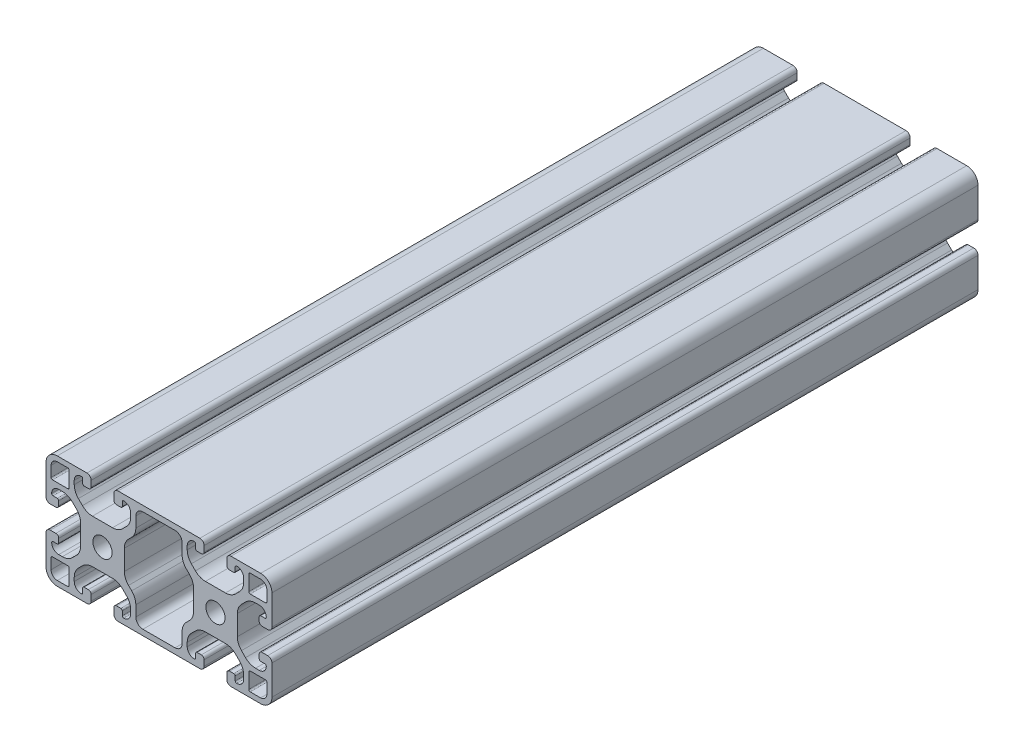
SolidWorks part; units mm, degrees
ref_plane "Plan de face" through (0, 0, 0) normal (0, 0, 1) x (1, 0, 0)
ref_plane "Plan de dessus" through (0, 0, 0) normal (0, 1, 0) x (1, 0, 0)
ref_plane "Plan de droite" through (0, 0, 0) normal (1, 0, 0) x (0, 0, -1)
ref_plane "Plan1" through (0, 0, 20) normal (0, 0, 1) x (1, 0, 0)
sketch "Esquisse1" plane through (0, 0, 20) normal (0, 0, 1) x (1, 0, 0)
  line L0 (66.5, 4.5) -> (65, 4.5)
  line L1 (64, 3.5) -> (64, 1.5)
  line L2 (65.5, 0) -> (76, 0)
  line L3 (80, 4) -> (80, 14.5)
  line L4 (78.5, 16) -> (76.5, 16)
  line L5 (75.5, 15) -> (75.5, 13.5)
  line L6 (76, 13) -> (77.5, 13)
  line L7 (75.5, 10) -> (74.1924, 10)
  line L8 (70.6569, 11.4645) -> (69.2145, 12.9069)
  line L9 (67.75, 16.4424) -> (67.75, 23.5576)
  line L10 (69.2145, 27.0931) -> (70.6569, 28.5355)
  line L11 (74.1924, 30) -> (75.5, 30)
  line L12 (77.5, 27) -> (76, 27)
  line L13 (75.5, 26.5) -> (75.5, 25)
  line L14 (76.5, 24) -> (78.5, 24)
  line L15 (80, 25.5) -> (80, 36)
  line L16 (76, 40) -> (65.5, 40)
  line L17 (64, 38.5) -> (64, 36.5)
  line L18 (65, 35.5) -> (66.5, 35.5)
  line L19 (67, 36) -> (67, 37.5)
  line L20 (70, 35.5) -> (70, 34.1924)
  line L21 (68.5355, 30.6569) -> (67.0931, 29.2145)
  line L22 (63.5576, 27.75) -> (56.4424, 27.75)
  line L23 (52.9069, 29.2145) -> (51.4645, 30.6569)
  line L24 (50, 34.1924) -> (50, 35.5)
  line L25 (53, 37.5) -> (53, 36)
  line L26 (53.5, 35.5) -> (55, 35.5)
  line L27 (56, 36.5) -> (56, 38.5)
  line L28 (54.5, 40) -> (25.5, 40)
  line L29 (24, 38.5) -> (24, 36.5)
  line L30 (25, 35.5) -> (26.5, 35.5)
  line L31 (27, 36) -> (27, 37.5)
  line L32 (30, 35.5) -> (30, 34.1924)
  line L33 (28.5355, 30.6569) -> (27.0931, 29.2145)
  line L34 (23.5576, 27.75) -> (16.4424, 27.75)
  line L35 (12.9069, 29.2145) -> (11.4645, 30.6569)
  line L36 (10, 34.1924) -> (10, 35.5)
  line L37 (13, 37.5) -> (13, 36)
  line L38 (13.5, 35.5) -> (15, 35.5)
  line L39 (16, 36.5) -> (16, 38.5)
  line L40 (14.5, 40) -> (4, 40)
  line L41 (0, 36) -> (0, 25.5)
  line L42 (1.5, 24) -> (3.5, 24)
  line L43 (4.5, 25) -> (4.5, 26.5)
  line L44 (4, 27) -> (2.5, 27)
  line L45 (4.5, 30) -> (5.8076, 30)
  line L46 (9.3431, 28.5355) -> (10.7855, 27.0931)
  line L47 (12.25, 23.5576) -> (12.25, 16.4424)
  line L48 (10.7855, 12.9069) -> (9.3431, 11.4645)
  line L49 (5.8076, 10) -> (4.5, 10)
  line L50 (2.5, 13) -> (4, 13)
  line L51 (4.5, 13.5) -> (4.5, 15)
  line L52 (3.5, 16) -> (1.5, 16)
  line L53 (0, 14.5) -> (0, 4)
  line L54 (4, 0) -> (14.5, 0)
  line L55 (16, 1.5) -> (16, 3.5)
  line L56 (15, 4.5) -> (13.5, 4.5)
  line L57 (13, 4) -> (13, 2.5)
  line L58 (10, 4.5) -> (10, 5.8076)
  line L59 (11.4645, 9.3431) -> (12.9069, 10.7855)
  line L60 (16.4424, 12.25) -> (23.5576, 12.25)
  line L61 (27.0931, 10.7855) -> (28.5355, 9.3431)
  line L62 (30, 5.8076) -> (30, 4.5)
  line L63 (27, 2.5) -> (27, 4)
  line L64 (26.5, 4.5) -> (25, 4.5)
  line L65 (24, 3.5) -> (24, 1.5)
  line L66 (25.5, 0) -> (54.5, 0)
  line L67 (56, 1.5) -> (56, 3.5)
  line L68 (55, 4.5) -> (53.5, 4.5)
  line L69 (53, 4) -> (53, 2.5)
  line L70 (50, 4.5) -> (50, 5.8076)
  line L71 (51.4645, 9.3431) -> (52.9069, 10.7855)
  line L72 (56.4424, 12.25) -> (63.5576, 12.25)
  line L73 (67.0931, 10.7855) -> (68.5355, 9.3431)
  line L74 (70, 5.8076) -> (70, 4.5)
  line L75 (67, 2.5) -> (67, 4)
  line L76 (31.8, 4.5) -> (31.8, 8.2503)
  line L77 (30.3355, 11.7858) -> (29.2145, 12.9069)
  line L78 (27.75, 16.4424) -> (27.75, 23.5576)
  line L79 (29.2145, 27.0931) -> (30.3355, 28.2142)
  line L80 (31.8, 31.7497) -> (31.8, 35.5)
  line L81 (34.3, 38) -> (45.7, 38)
  line L82 (48.2, 35.5) -> (48.2, 31.7497)
  line L83 (49.6645, 28.2142) -> (50.7855, 27.0931)
  line L84 (52.25, 23.5576) -> (52.25, 16.4424)
  line L85 (50.7855, 12.9069) -> (49.6645, 11.7858)
  line L86 (48.2, 8.2503) -> (48.2, 4.5)
  line L87 (45.7, 2) -> (34.3, 2)
  line L88 (7.7, 1.8) -> (4, 1.8)
  line L89 (1.8, 4) -> (1.8, 7.7)
  line L90 (2.3, 8.2) -> (7.7, 8.2)
  line L91 (8.2, 7.7) -> (8.2, 2.3)
  line L92 (72.3, 38.2) -> (76, 38.2)
  line L93 (78.2, 36) -> (78.2, 32.3)
  line L94 (77.7, 31.8) -> (72.3, 31.8)
  line L95 (71.8, 32.3) -> (71.8, 37.7)
  line L96 (78.2, 7.7) -> (78.2, 4)
  line L97 (76, 1.8) -> (72.3, 1.8)
  line L98 (71.8, 2.3) -> (71.8, 7.7)
  line L99 (72.3, 8.2) -> (77.7, 8.2)
  line L100 (1.8, 32.3) -> (1.8, 36)
  line L101 (4, 38.2) -> (7.7, 38.2)
  line L102 (8.2, 37.7) -> (8.2, 32.3)
  line L103 (7.7, 31.8) -> (2.3, 31.8)
  arc A0 (67, 4) -> (66.5, 4.5) centre (66.5, 4) ccw
  arc A1 (65, 4.5) -> (64, 3.5) centre (65, 3.5) ccw
  arc A2 (64, 1.5) -> (65.5, 0) centre (65.5, 1.5) ccw
  arc A3 (76, 0) -> (80, 4) centre (76, 4) ccw
  arc A4 (80, 14.5) -> (78.5, 16) centre (78.5, 14.5) ccw
  arc A5 (76.5, 16) -> (75.5, 15) centre (76.5, 15) ccw
  arc A6 (75.5, 13.5) -> (76, 13) centre (76, 13.5) ccw
  arc A7 (77.5, 13) -> (78, 12.5) centre (77.5, 12.5) cw
  arc A8 (78, 12.5) -> (75.5, 10) centre (75.5, 12.5) cw
  arc A9 (74.1924, 10) -> (70.6569, 11.4645) centre (74.1924, 15) cw
  arc A10 (69.2145, 12.9069) -> (67.75, 16.4424) centre (72.75, 16.4424) cw
  arc A11 (67.75, 23.5576) -> (69.2145, 27.0931) centre (72.75, 23.5576) cw
  arc A12 (70.6569, 28.5355) -> (74.1924, 30) centre (74.1924, 25) cw
  arc A13 (75.5, 30) -> (78, 27.5) centre (75.5, 27.5) cw
  arc A14 (78, 27.5) -> (77.5, 27) centre (77.5, 27.5) cw
  arc A15 (76, 27) -> (75.5, 26.5) centre (76, 26.5) ccw
  arc A16 (75.5, 25) -> (76.5, 24) centre (76.5, 25) ccw
  arc A17 (78.5, 24) -> (80, 25.5) centre (78.5, 25.5) ccw
  arc A18 (80, 36) -> (76, 40) centre (76, 36) ccw
  arc A19 (65.5, 40) -> (64, 38.5) centre (65.5, 38.5) ccw
  arc A20 (64, 36.5) -> (65, 35.5) centre (65, 36.5) ccw
  arc A21 (66.5, 35.5) -> (67, 36) centre (66.5, 36) ccw
  arc A22 (67, 37.5) -> (67.5, 38) centre (67.5, 37.5) cw
  arc A23 (67.5, 38) -> (70, 35.5) centre (67.5, 35.5) cw
  arc A24 (70, 34.1924) -> (68.5355, 30.6569) centre (65, 34.1924) cw
  arc A25 (67.0931, 29.2145) -> (63.5576, 27.75) centre (63.5576, 32.75) cw
  arc A26 (56.4424, 27.75) -> (52.9069, 29.2145) centre (56.4424, 32.75) cw
  arc A27 (51.4645, 30.6569) -> (50, 34.1924) centre (55, 34.1924) cw
  arc A28 (50, 35.5) -> (52.5, 38) centre (52.5, 35.5) cw
  arc A29 (52.5, 38) -> (53, 37.5) centre (52.5, 37.5) cw
  arc A30 (53, 36) -> (53.5, 35.5) centre (53.5, 36) ccw
  arc A31 (55, 35.5) -> (56, 36.5) centre (55, 36.5) ccw
  arc A32 (56, 38.5) -> (54.5, 40) centre (54.5, 38.5) ccw
  arc A33 (25.5, 40) -> (24, 38.5) centre (25.5, 38.5) ccw
  arc A34 (24, 36.5) -> (25, 35.5) centre (25, 36.5) ccw
  arc A35 (26.5, 35.5) -> (27, 36) centre (26.5, 36) ccw
  arc A36 (27, 37.5) -> (27.5, 38) centre (27.5, 37.5) cw
  arc A37 (27.5, 38) -> (30, 35.5) centre (27.5, 35.5) cw
  arc A38 (30, 34.1924) -> (28.5355, 30.6569) centre (25, 34.1924) cw
  arc A39 (27.0931, 29.2145) -> (23.5576, 27.75) centre (23.5576, 32.75) cw
  arc A40 (16.4424, 27.75) -> (12.9069, 29.2145) centre (16.4424, 32.75) cw
  arc A41 (11.4645, 30.6569) -> (10, 34.1924) centre (15, 34.1924) cw
  arc A42 (10, 35.5) -> (12.5, 38) centre (12.5, 35.5) cw
  arc A43 (12.5, 38) -> (13, 37.5) centre (12.5, 37.5) cw
  arc A44 (13, 36) -> (13.5, 35.5) centre (13.5, 36) ccw
  arc A45 (15, 35.5) -> (16, 36.5) centre (15, 36.5) ccw
  arc A46 (16, 38.5) -> (14.5, 40) centre (14.5, 38.5) ccw
  arc A47 (4, 40) -> (0, 36) centre (4, 36) ccw
  arc A48 (0, 25.5) -> (1.5, 24) centre (1.5, 25.5) ccw
  arc A49 (3.5, 24) -> (4.5, 25) centre (3.5, 25) ccw
  arc A50 (4.5, 26.5) -> (4, 27) centre (4, 26.5) ccw
  arc A51 (2.5, 27) -> (2, 27.5) centre (2.5, 27.5) cw
  arc A52 (2, 27.5) -> (4.5, 30) centre (4.5, 27.5) cw
  arc A53 (5.8076, 30) -> (9.3431, 28.5355) centre (5.8076, 25) cw
  arc A54 (10.7855, 27.0931) -> (12.25, 23.5576) centre (7.25, 23.5576) cw
  arc A55 (12.25, 16.4424) -> (10.7855, 12.9069) centre (7.25, 16.4424) cw
  arc A56 (9.3431, 11.4645) -> (5.8076, 10) centre (5.8076, 15) cw
  arc A57 (4.5, 10) -> (2, 12.5) centre (4.5, 12.5) cw
  arc A58 (2, 12.5) -> (2.5, 13) centre (2.5, 12.5) cw
  arc A59 (4, 13) -> (4.5, 13.5) centre (4, 13.5) ccw
  arc A60 (4.5, 15) -> (3.5, 16) centre (3.5, 15) ccw
  arc A61 (1.5, 16) -> (0, 14.5) centre (1.5, 14.5) ccw
  arc A62 (0, 4) -> (4, 0) centre (4, 4) ccw
  arc A63 (14.5, 0) -> (16, 1.5) centre (14.5, 1.5) ccw
  arc A64 (16, 3.5) -> (15, 4.5) centre (15, 3.5) ccw
  arc A65 (13.5, 4.5) -> (13, 4) centre (13.5, 4) ccw
  arc A66 (13, 2.5) -> (12.5, 2) centre (12.5, 2.5) cw
  arc A67 (12.5, 2) -> (10, 4.5) centre (12.5, 4.5) cw
  arc A68 (10, 5.8076) -> (11.4645, 9.3431) centre (15, 5.8076) cw
  arc A69 (12.9069, 10.7855) -> (16.4424, 12.25) centre (16.4424, 7.25) cw
  arc A70 (23.5576, 12.25) -> (27.0931, 10.7855) centre (23.5576, 7.25) cw
  arc A71 (28.5355, 9.3431) -> (30, 5.8076) centre (25, 5.8076) cw
  arc A72 (30, 4.5) -> (27.5, 2) centre (27.5, 4.5) cw
  arc A73 (27.5, 2) -> (27, 2.5) centre (27.5, 2.5) cw
  arc A74 (27, 4) -> (26.5, 4.5) centre (26.5, 4) ccw
  arc A75 (25, 4.5) -> (24, 3.5) centre (25, 3.5) ccw
  arc A76 (24, 1.5) -> (25.5, 0) centre (25.5, 1.5) ccw
  arc A77 (54.5, 0) -> (56, 1.5) centre (54.5, 1.5) ccw
  arc A78 (56, 3.5) -> (55, 4.5) centre (55, 3.5) ccw
  arc A79 (53.5, 4.5) -> (53, 4) centre (53.5, 4) ccw
  arc A80 (53, 2.5) -> (52.5, 2) centre (52.5, 2.5) cw
  arc A81 (52.5, 2) -> (50, 4.5) centre (52.5, 4.5) cw
  arc A82 (50, 5.8076) -> (51.4645, 9.3431) centre (55, 5.8076) cw
  arc A83 (52.9069, 10.7855) -> (56.4424, 12.25) centre (56.4424, 7.25) cw
  arc A84 (63.5576, 12.25) -> (67.0931, 10.7855) centre (63.5576, 7.25) cw
  arc A85 (68.5355, 9.3431) -> (70, 5.8076) centre (65, 5.8076) cw
  arc A86 (70, 4.5) -> (67.5, 2) centre (67.5, 4.5) cw
  arc A87 (67.5, 2) -> (67, 2.5) centre (67.5, 2.5) cw
  circle A88 centre (20, 20) radius 3.4
  circle A89 centre (60, 20) radius 3.4
  arc A90 (34.3, 2) -> (31.8, 4.5) centre (34.3, 4.5) cw
  arc A91 (31.8, 8.2503) -> (30.3355, 11.7858) centre (26.8, 8.2503) ccw
  arc A92 (29.2145, 12.9069) -> (27.75, 16.4424) centre (32.75, 16.4424) cw
  arc A93 (27.75, 23.5576) -> (29.2145, 27.0931) centre (32.75, 23.5576) cw
  arc A94 (30.3355, 28.2142) -> (31.8, 31.7497) centre (26.8, 31.7497) ccw
  arc A95 (31.8, 35.5) -> (34.3, 38) centre (34.3, 35.5) cw
  arc A96 (45.7, 38) -> (48.2, 35.5) centre (45.7, 35.5) cw
  arc A97 (48.2, 31.7497) -> (49.6645, 28.2142) centre (53.2, 31.7497) ccw
  arc A98 (50.7855, 27.0931) -> (52.25, 23.5576) centre (47.25, 23.5576) cw
  arc A99 (52.25, 16.4424) -> (50.7855, 12.9069) centre (47.25, 16.4424) cw
  arc A100 (49.6645, 11.7858) -> (48.2, 8.2503) centre (53.2, 8.2503) ccw
  arc A101 (48.2, 4.5) -> (45.7, 2) centre (45.7, 4.5) cw
  arc A102 (8.2, 2.3) -> (7.7, 1.8) centre (7.7, 2.3) cw
  arc A103 (4, 1.8) -> (1.8, 4) centre (4, 4) cw
  arc A104 (1.8, 7.7) -> (2.3, 8.2) centre (2.3, 7.7) cw
  arc A105 (7.7, 8.2) -> (8.2, 7.7) centre (7.7, 7.7) cw
  arc A106 (71.8, 37.7) -> (72.3, 38.2) centre (72.3, 37.7) cw
  arc A107 (76, 38.2) -> (78.2, 36) centre (76, 36) cw
  arc A108 (78.2, 32.3) -> (77.7, 31.8) centre (77.7, 32.3) cw
  arc A109 (72.3, 31.8) -> (71.8, 32.3) centre (72.3, 32.3) cw
  arc A110 (77.7, 8.2) -> (78.2, 7.7) centre (77.7, 7.7) cw
  arc A111 (78.2, 4) -> (76, 1.8) centre (76, 4) cw
  arc A112 (72.3, 1.8) -> (71.8, 2.3) centre (72.3, 2.3) cw
  arc A113 (71.8, 7.7) -> (72.3, 8.2) centre (72.3, 7.7) cw
  arc A114 (2.3, 31.8) -> (1.8, 32.3) centre (2.3, 32.3) cw
  arc A115 (1.8, 36) -> (4, 38.2) centre (4, 36) cw
  arc A116 (7.7, 38.2) -> (8.2, 37.7) centre (7.7, 37.7) cw
  arc A117 (8.2, 32.3) -> (7.7, 31.8) centre (7.7, 32.3) cw
extrude "Boss.-Extru.1" add sketch "Esquisse1" against normal blind 250
